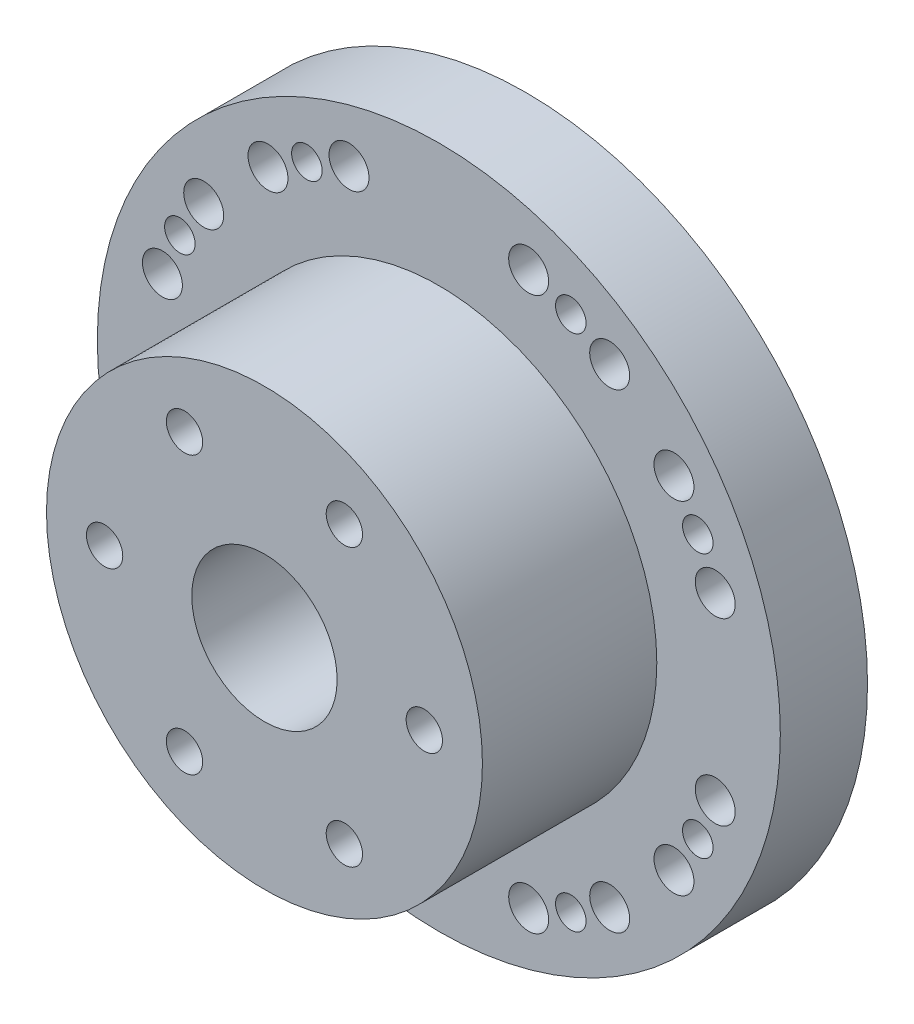
SolidWorks part; units mm, degrees
material "7075-T6 (SN)"
ref_plane "前视基准面" through (0, 0, 0) normal (0, 0, 1) x (1, 0, 0)
ref_plane "上视基准面" through (0, 0, 0) normal (0, 1, 0) x (1, 0, 0)
ref_plane "右视基准面" through (0, 0, 0) normal (1, 0, 0) x (0, 0, -1)
other "Configuration Table"
sketch "草图1" plane through (0, 0, 0) normal (0, 0, 1) x (1, 0, 0)
  circle A0 centre (0, 0) radius 47
extrude "凸台-拉伸1" add sketch "草图1" along normal blind 12
sketch "草图2" plane through (0, 0, 0) normal (0, 0, 1) x (1, 0, 0)
  circle A0 centre (0, 0) radius 30
extrude "凸台-拉伸2" add sketch "草图2" along normal blind 36
sketch "草图3" plane through (0, 0, 0) normal (0, 0, -1) x (-1, 0, 0)
  circle A0 centre (0, 0) radius 10
extrude "切除-拉伸1" cut sketch "草图3" against normal blind 37
sketch "草图4" plane through (0, 0, 0) normal (0, 0, -1) x (-1, 0, 0)
  circle A0 centre (-38.043, -12.3584) radius 2.75
  circle A1 centre (-32.3621, -23.5095) radius 2.75
  circle A2 centre (-23.5133, -32.3593) radius 2.75
  circle A3 centre (-12.3629, -38.0415) radius 2.75
  circle A4 centre (12.3584, -38.043) radius 2.75
  circle A5 centre (23.5095, -32.3621) radius 2.75
  circle A6 centre (32.3593, -23.5133) radius 2.75
  circle A7 centre (38.0415, -12.3629) radius 2.75
  circle A8 centre (38.043, 12.3584) radius 2.75
  circle A9 centre (32.3621, 23.5095) radius 2.75
  circle A10 centre (23.5133, 32.3593) radius 2.75
  circle A11 centre (12.3629, 38.0415) radius 2.75
  circle A12 centre (-12.3584, 38.043) radius 2.75
  circle A13 centre (-23.5095, 32.3621) radius 2.75
  circle A14 centre (-32.3593, 23.5133) radius 2.75
  circle A15 centre (-38.0415, 12.3629) radius 2.75
  circle A16 centre (-35.6403, 18.1596) radius 2.1
  circle A17 centre (-18.1596, 35.6403) radius 2.1
  circle A18 centre (18.1596, 35.6403) radius 2.1
  circle A19 centre (35.6403, 18.1596) radius 2.1
  circle A20 centre (35.6403, -18.1596) radius 2.1
  circle A21 centre (18.1596, -35.6403) radius 2.1
  circle A22 centre (-18.1596, -35.6403) radius 2.1
  circle A23 centre (-35.6403, -18.1596) radius 2.1
extrude "切除-拉伸2" cut sketch "草图4" against normal blind 13
sketch "草图5" plane through (0, 0, 36) normal (0, 0, 1) x (1, 0, 0)
  circle A0 centre (22, 0) radius 2.5
  circle A1 centre (11, 19.0526) radius 2.5
  circle A2 centre (-11, 19.0526) radius 2.5
  circle A3 centre (-22, 0) radius 2.5
  circle A4 centre (-11, -19.0526) radius 2.5
  circle A5 centre (11, -19.0526) radius 2.5
extrude "切除-拉伸3" cut sketch "草图5" against normal blind 14
